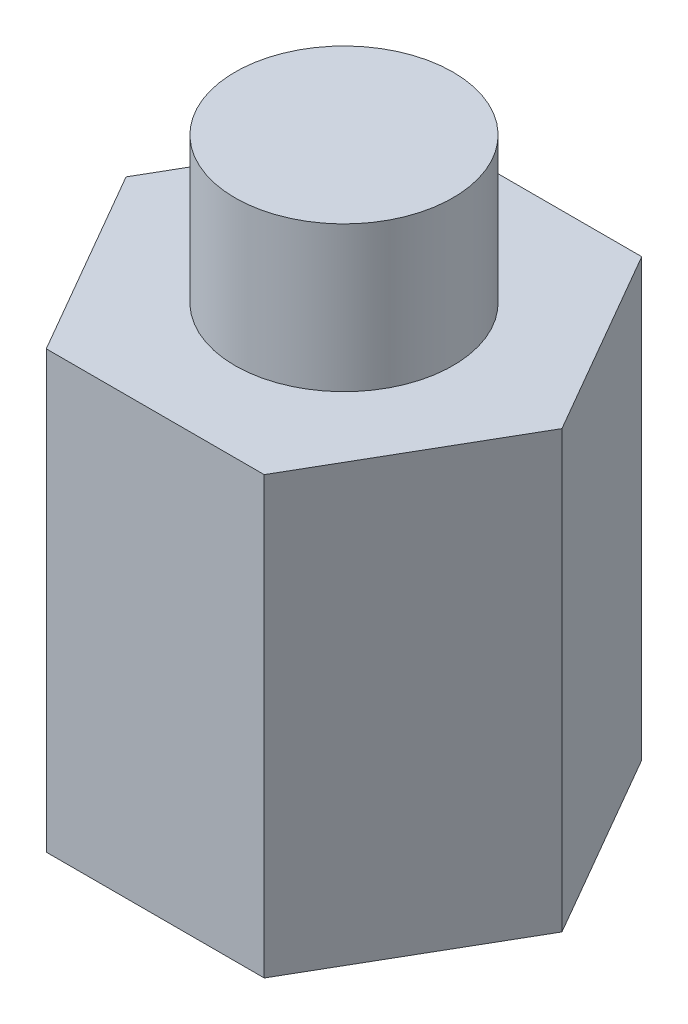
SolidWorks part; units mm, degrees
ref_plane "前视基准面" through (0, 0, 0) normal (0, 0, 1) x (1, 0, 0)
ref_plane "上视基准面" through (0, 0, 0) normal (0, 1, 0) x (1, 0, 0)
ref_plane "右视基准面" through (0, 0, 0) normal (1, 0, 0) x (0, 0, -1)
other "Configuration Table"
sketch "草图1" plane through (0, 0, 0) normal (0, 1, 0) x (1, 0, 0)
  line L1 (3, 0) -> (1.5, 2.5981)
  line L2 (1.5, 2.5981) -> (-1.5, 2.5981)
  line L3 (-1.5, 2.5981) -> (-3, 0)
  line L4 (-3, 0) -> (-1.5, -2.5981)
  line L5 (-1.5, -2.5981) -> (1.5, -2.5981)
  line L6 (1.5, -2.5981) -> (3, 0)
  circle A0 centre (0, 0) radius 2.5981 construction
  circle A1 centre (0, 0) radius 1.5
  dimension "D2" = 3
  dimension "D1" = 3
extrude "凸台-拉伸1" add sketch "草图1" along normal blind 6
sketch "草图2" plane through (0, 6, 0) normal (0, 1, 0) x (1, 0, 0)
  circle A0 centre (0, 0) radius 1.5
  dimension "D1" = 3
extrude "凸台-拉伸2" add sketch "草图2" along normal blind 2 and the other way blind 1 contours A0
